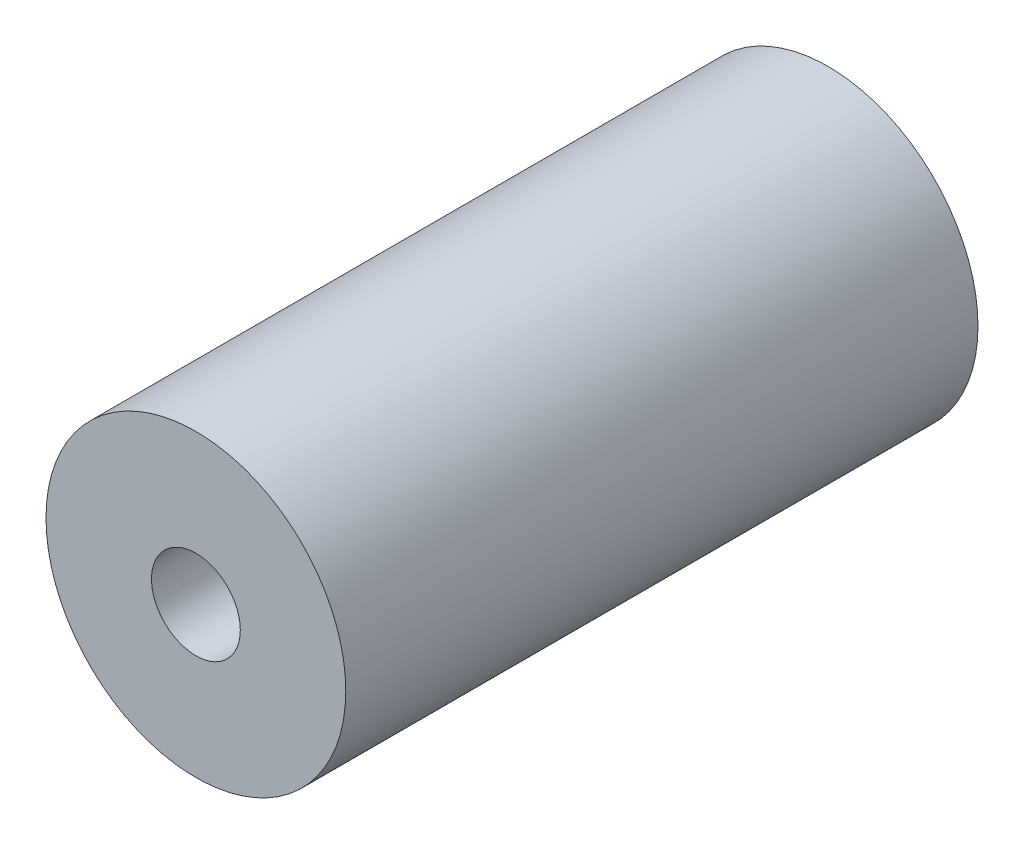
SolidWorks part; units mm, degrees
material "Cesaroni C Star Propellant"
ref_plane "Front Plane" through (0, 0, 0) normal (1, 0, 0) x (0, 1, 0)
ref_plane "Top Plane" through (0, 0, 0) normal (0, 0, 1) x (0, 1, 0)
ref_plane "Right Plane" through (0, 0, 0) normal (0, 1, 0) x (-1, 0, 0)
sketch "Sketch1" plane through (0, 0, 0) normal (0, 0, 1) x (0, 1, 0)
  circle A0 centre (0, 0) radius 32.15
  circle A1 centre (0, 0) radius 9.525
  dimension "D1" = 64.3
  dimension "D2" = 19.05
extrude "Boss-Extrude1" add sketch "Sketch1" along normal blind 135.6
